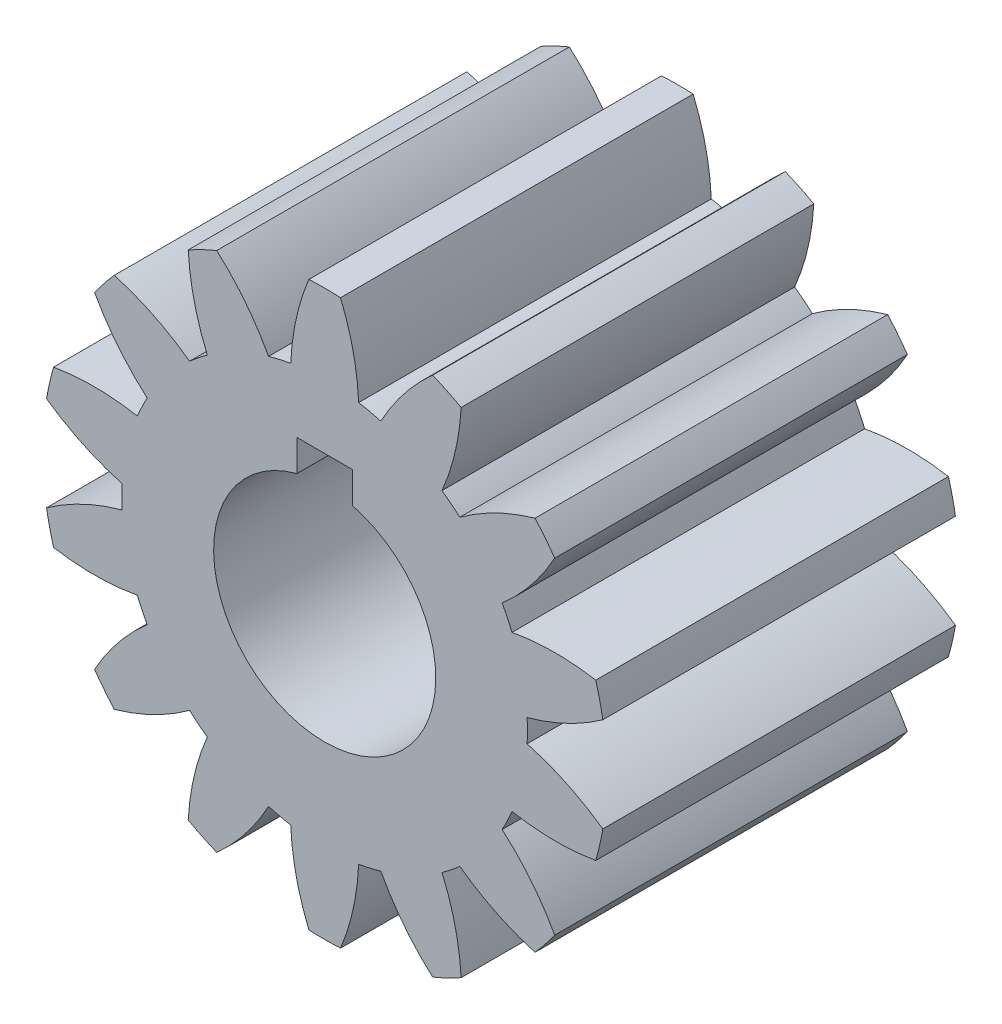
SolidWorks part; units mm, degrees
ref_plane "Front" through (0, 0, 0) normal (0, 0, 1) x (1, 0, 0)
ref_plane "Top" through (0, 0, 0) normal (0, 1, 0) x (1, 0, 0)
ref_plane "Right" through (0, 0, 0) normal (1, 0, 0) x (0, 0, -1)
sketch "Sketch1" plane through (0, 0, 0) normal (0, 0, 1) x (1, 0, 0)
  line L0 (0, 0) -> (0, 15.3026) construction
  line L1 (0, 0) -> (2.0216, 7.0171) construction
  arc A0 (3.8881, 9.3866) -> (2.0216, 7.0171) centre (9.6274, 2.9458) ccw
  arc A1 (4.9146, 8.8923) -> (3.8881, 9.3866) centre (0, 0) ccw
  arc A2 (4.2257, 5.9556) -> (4.9146, 8.8923) centre (-3.6995, 9.3637) ccw
  arc A3 (4.866, 5.4451) -> (4.2257, 5.9556) centre (0, 0) ccw
  arc A4 (7.5757, 6.7701) -> (4.866, 5.4451) centre (9.9522, -1.5231) ccw
  arc A5 (8.2861, 5.8793) -> (7.5757, 6.7701) centre (0, 0) ccw
  arc A6 (-0.5697, 10.144) -> (-1.2232, 7.1993) centre (7.3959, 6.8313) ccw
  arc A7 (0.5697, 10.144) -> (-0.5697, 10.144) centre (0, 0) ccw
  arc A8 (1.2232, 7.1993) -> (0.5697, 10.144) centre (-7.3959, 6.8313) ccw
  arc A9 (2.0216, 7.0171) -> (1.2232, 7.1993) centre (0, 0) ccw
  arc A10 (6.3913, 3.5324) -> (8.2861, 5.8793) centre (0.7297, 10.0416) ccw
  arc A11 (6.7466, 2.7945) -> (6.3913, 3.5324) centre (0, 0) ccw
  arc A12 (9.7629, 2.8126) -> (6.7466, 2.7945) centre (8.3058, -5.6903) ccw
  arc A13 (10.0164, 1.7019) -> (9.7629, 2.8126) centre (0, 0) ccw
  arc A14 (7.291, 0.4095) -> (10.0164, 1.7019) centre (5.0143, 8.7306) ccw
  arc A15 (7.291, -0.4095) -> (7.291, 0.4095) centre (0, 0) ccw
  arc A16 (10.0164, -1.7019) -> (7.291, -0.4095) centre (5.0143, -8.7306) ccw
  arc A17 (9.7629, -2.8126) -> (10.0164, -1.7019) centre (0, 0) ccw
  arc A18 (6.7466, -2.7945) -> (9.7629, -2.8126) centre (8.3058, 5.6903) ccw
  arc A19 (6.3913, -3.5324) -> (6.7466, -2.7945) centre (0, 0) ccw
  arc A20 (8.2861, -5.8793) -> (6.3913, -3.5324) centre (0.7297, -10.0416) ccw
  arc A21 (7.5757, -6.7701) -> (8.2861, -5.8793) centre (0, 0) ccw
  arc A22 (4.866, -5.4451) -> (7.5757, -6.7701) centre (9.9522, 1.5231) ccw
  arc A23 (4.2257, -5.9556) -> (4.866, -5.4451) centre (0, 0) ccw
  arc A24 (4.9146, -8.8923) -> (4.2257, -5.9556) centre (-3.6995, -9.3637) ccw
  arc A25 (3.8881, -9.3866) -> (4.9146, -8.8923) centre (0, 0) ccw
  arc A26 (2.0216, -7.0171) -> (3.8881, -9.3866) centre (9.6274, -2.9458) ccw
  arc A27 (1.2232, -7.1993) -> (2.0216, -7.0171) centre (0, 0) ccw
  arc A28 (0.5697, -10.144) -> (1.2232, -7.1993) centre (-7.3959, -6.8313) ccw
  arc A29 (-0.5697, -10.144) -> (0.5697, -10.144) centre (0, 0) ccw
  arc A30 (-1.2232, -7.1993) -> (-0.5697, -10.144) centre (7.3959, -6.8313) ccw
  arc A31 (-2.0216, -7.0171) -> (-1.2232, -7.1993) centre (0, 0) ccw
  arc A32 (-3.8881, -9.3866) -> (-2.0216, -7.0171) centre (-9.6274, -2.9458) ccw
  arc A33 (-4.9146, -8.8923) -> (-3.8881, -9.3866) centre (0, 0) ccw
  arc A34 (-4.2257, -5.9556) -> (-4.9146, -8.8923) centre (3.6995, -9.3637) ccw
  arc A35 (-4.866, -5.4451) -> (-4.2257, -5.9556) centre (0, 0) ccw
  arc A36 (-7.5757, -6.7701) -> (-4.866, -5.4451) centre (-9.9522, 1.5231) ccw
  arc A37 (-8.2861, -5.8793) -> (-7.5757, -6.7701) centre (0, 0) ccw
  arc A38 (-6.3913, -3.5324) -> (-8.2861, -5.8793) centre (-0.7297, -10.0416) ccw
  arc A39 (-6.7466, -2.7945) -> (-6.3913, -3.5324) centre (0, 0) ccw
  arc A40 (-9.7629, -2.8126) -> (-6.7466, -2.7945) centre (-8.3058, 5.6903) ccw
  arc A41 (-10.0164, -1.7019) -> (-9.7629, -2.8126) centre (0, 0) ccw
  arc A42 (-7.291, -0.4095) -> (-10.0164, -1.7019) centre (-5.0143, -8.7306) ccw
  arc A43 (-7.291, 0.4095) -> (-7.291, -0.4095) centre (0, 0) ccw
  arc A44 (-10.0164, 1.7019) -> (-7.291, 0.4095) centre (-5.0143, 8.7306) ccw
  arc A45 (-9.7629, 2.8126) -> (-10.0164, 1.7019) centre (0, 0) ccw
  arc A46 (-6.7466, 2.7945) -> (-9.7629, 2.8126) centre (-8.3058, -5.6903) ccw
  arc A47 (-6.3913, 3.5324) -> (-6.7466, 2.7945) centre (0, 0) ccw
  arc A48 (-8.2861, 5.8793) -> (-6.3913, 3.5324) centre (-0.7297, 10.0416) ccw
  arc A49 (-7.5757, 6.7701) -> (-8.2861, 5.8793) centre (0, 0) ccw
  arc A50 (-4.866, 5.4451) -> (-7.5757, 6.7701) centre (-9.9522, -1.5231) ccw
  arc A51 (-4.2257, 5.9556) -> (-4.866, 5.4451) centre (0, 0) ccw
  arc A52 (-4.9146, 8.8923) -> (-4.2257, 5.9556) centre (3.6995, 9.3637) ccw
  arc A53 (-3.8881, 9.3866) -> (-4.9146, 8.8923) centre (0, 0) ccw
  arc A54 (-2.0216, 7.0171) -> (-3.8881, 9.3866) centre (-9.6274, 2.9458) ccw
  arc A55 (-1.2232, 7.1993) -> (-2.0216, 7.0171) centre (0, 0) ccw
  dimension "D1" = 10.16
  dimension "D2" = 7.3025
  dimension "D3" = 8.627
  dimension "D6" = 2.9607
  dimension "D4" = 16.071
  dimension "D7" = 1.1394
extrude "Extrude1" add sketch "Sketch1" along normal mid plane 12.7
sketch "Sketch2" plane through (0, 0, 0) normal (0, 0, 1) x (1, 0, 0)
  line L0 (-1, 3.873) -> (-1, 5)
  line L1 (1, 5) -> (-1, 5)
  line L2 (1, 3.873) -> (1, 5)
  line L3 (0, 0) -> (0, 7.2221) construction
  arc A0 (-1, 3.873) -> (1, 3.873) centre (0, 0) ccw
  dimension "D1" = 4
  dimension "D2" = 2
  dimension "D3" = 1.127
extrude "Extrude2" cut sketch "Sketch2" against normal through all and the other way through all
